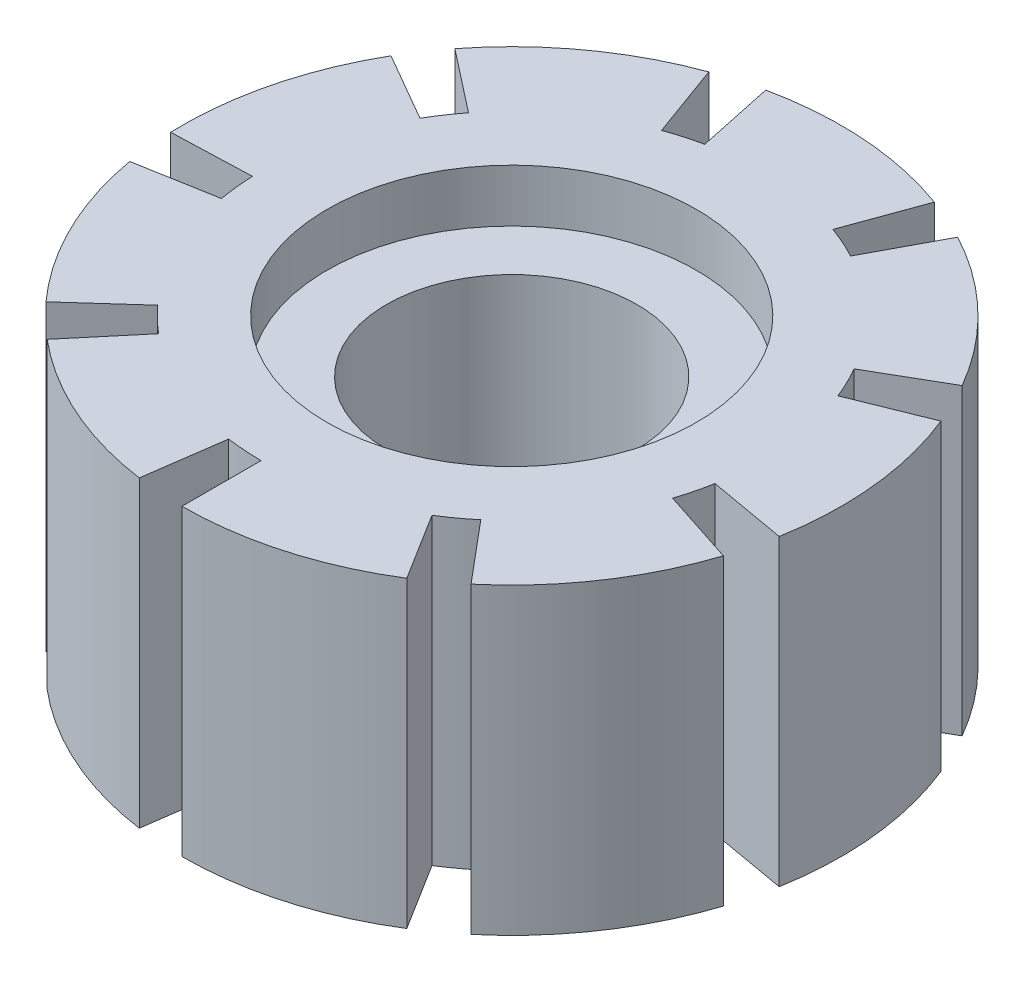
SolidWorks part; units mm, degrees
ref_plane "Front Plane" through (0, 0, 0) normal (0, 0, 1) x (1, 0, 0)
ref_plane "Top Plane" through (0, 0, 0) normal (0, 1, 0) x (1, 0, 0)
ref_plane "Right Plane" through (0, 0, 0) normal (1, 0, 0) x (0, 0, -1)
sketch "Sketch1" plane through (0, 0, 0) normal (0, 1, 0) x (1, 0, 0)
  circle A0 centre (0, 0) radius 9.5
  circle A1 centre (0, 0) radius 25
  dimension "D1" = 19
  dimension "D2" = 50
extrude "Boss-Extrude1" add sketch "Sketch1" along normal blind 15
sketch "Sketch4" plane through (0, 0, 0) normal (0, 0, 1) x (1, 0, 0)
  line L0 (-25, 7.5) -> (29.7231, 7.5) construction
  line L1 (-25, 15) -> (-25, 0) construction
sketch "Sketch2" plane through (0, 15, 0) normal (0, 1, 0) x (1, 0, 0)
  circle A0 centre (0, 0) radius 14
  circle A1 centre (0, 0) radius 25
  dimension "D1" = 28
extrude "Boss-Extrude2" add sketch "Sketch2" along normal blind 4
ref_plane "Plane1" through (0, 7.5, 0) normal (0, 1, 0) x (1, 0, 0)
mirror "Mirror1" about plane through (0, 7.5, 0) normal (0, 1, 0) of "Boss-Extrude2"
sketch "Sketch6" plane through (0, -4, 0) normal (0, -1, 0) x (1, 0, 0)
  line L0 (-3.4793, 24.7567) -> (-2.6443, 18.8151)
  line L1 (0, 19) -> (0, 25)
  arc A0 (-3.4793, 24.7567) -> (0, 25) centre (0, 0) cw
  circle A1 centre (0, 0) radius 25 construction
  arc A2 (-2.6443, 18.8151) -> (0, 19) centre (0, 0) cw
  dimension "D3" = 19
  dimension "D1" = 8
  dimension "D2" = 6
extrude "Cut-Extrude1" cut sketch "Sketch6" against normal through all
pattern_circular "CirPattern1" count 9 over 360 about axis through (0, 0, 0) along (0, 1, 0) of "Cut-Extrude1"
